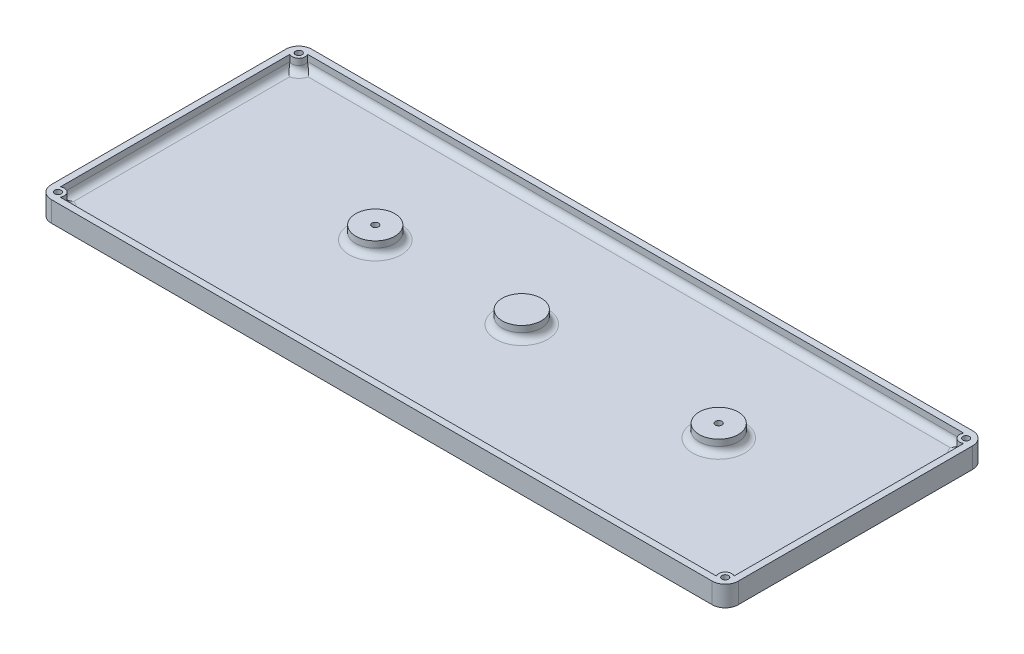
SolidWorks part; units mm, degrees
ref_plane "Front Plane" through (0, 0, 0) normal (0, 0, 1) x (1, 0, 0)
ref_plane "Top Plane" through (0, 0, 0) normal (0, 1, 0) x (1, 0, 0)
ref_plane "Right Plane" through (0, 0, 0) normal (1, 0, 0) x (0, 0, -1)
sketch "Sketch1" plane through (0, 0, 0) normal (0, 1, 0) x (1, 0, 0)
  line L1 (-128.905, 50.8) -> (128.905, 50.8)
  line L2 (-133.985, 45.72) -> (-133.985, -45.72)
  line L3 (-128.905, -50.8) -> (128.905, -50.8)
  line L4 (133.985, 45.72) -> (133.985, -45.72)
  line L5 (-133.985, 50.8) -> (133.985, -50.8) construction
  line L6 (-133.985, -50.8) -> (133.985, 50.8) construction
  arc A0 (-133.985, -45.72) -> (-128.905, -50.8) centre (-128.905, -45.72) ccw
  arc A1 (128.905, -50.8) -> (133.985, -45.72) centre (128.905, -45.72) ccw
  arc A2 (128.905, 50.8) -> (133.985, 45.72) centre (128.905, 45.72) cw
  arc A3 (-128.905, 50.8) -> (-133.985, 45.72) centre (-128.905, 45.72) ccw
  point P0 (0, 0)
  dimension "D3" = 5.08
  dimension "D1" = 101.6
  dimension "D2" = 267.97
extrude "Boss-Extrude1" add sketch "Sketch1" along normal blind 3
sketch "Sketch2" plane through (0, 3, 0) normal (0, 1, 0) x (1, 0, 0)
  line L8 (-128.905, -48.26) -> (128.905, -48.26)
  line L9 (131.445, -45.72) -> (131.445, 45.72)
  line L10 (128.905, 48.26) -> (-128.905, 48.26)
  line L11 (-131.445, 45.72) -> (-131.445, -45.72)
  line L12 (-128.905, -48.26) -> (128.905, -48.26)
  line L13 (131.445, -45.72) -> (131.445, 45.72)
  line L14 (128.905, 48.26) -> (-128.905, 48.26)
  line L15 (-131.445, 45.72) -> (-131.445, -45.72)
  line L20 (-128.905, -50.8) -> (128.905, -50.8)
  line L21 (133.985, -45.72) -> (133.985, 45.72)
  line L22 (128.905, 50.8) -> (-128.905, 50.8)
  line L23 (-133.985, 45.72) -> (-133.985, -45.72)
  line L24 (-128.905, -50.8) -> (128.905, -50.8)
  line L25 (133.985, -45.72) -> (133.985, 45.72)
  line L26 (128.905, 50.8) -> (-128.905, 50.8)
  line L27 (-133.985, 45.72) -> (-133.985, -45.72)
  arc A8 (-131.445, -45.72) -> (-128.905, -48.26) centre (-128.905, -45.72) ccw
  arc A9 (128.905, -48.26) -> (131.445, -45.72) centre (128.905, -45.72) ccw
  arc A10 (131.445, 45.72) -> (128.905, 48.26) centre (128.905, 45.72) ccw
  arc A11 (-128.905, 48.26) -> (-131.445, 45.72) centre (-128.905, 45.72) ccw
  arc A12 (-131.445, -45.72) -> (-128.905, -48.26) centre (-128.905, -45.72) ccw
  arc A13 (128.905, -48.26) -> (131.445, -45.72) centre (128.905, -45.72) ccw
  arc A14 (131.445, 45.72) -> (128.905, 48.26) centre (128.905, 45.72) ccw
  arc A15 (-128.905, 48.26) -> (-131.445, 45.72) centre (-128.905, 45.72) ccw
  arc A20 (-133.985, -45.72) -> (-128.905, -50.8) centre (-128.905, -45.72) ccw
  arc A21 (128.905, -50.8) -> (133.985, -45.72) centre (128.905, -45.72) ccw
  arc A22 (133.985, 45.72) -> (128.905, 50.8) centre (128.905, 45.72) ccw
  arc A23 (-128.905, 50.8) -> (-133.985, 45.72) centre (-128.905, 45.72) ccw
  arc A24 (-133.985, -45.72) -> (-128.905, -50.8) centre (-128.905, -45.72) ccw
  arc A25 (128.905, -50.8) -> (133.985, -45.72) centre (128.905, -45.72) ccw
  arc A26 (133.985, 45.72) -> (128.905, 50.8) centre (128.905, 45.72) ccw
  arc A27 (-128.905, 50.8) -> (-133.985, 45.72) centre (-128.905, 45.72) ccw
  dimension "D1" = 2.54
  dimension "D2" = 0
extrude "Boss-Extrude2" add sketch "Sketch2" along normal blind 5
sketch "Sketch3" plane through (0, 3, 0) normal (0, 1, 0) x (1, 0, 0)
  line L0 (-128.905, -50.8) -> (128.905, -50.8) construction
  line L1 (-133.985, 45.72) -> (-133.985, -45.72) construction
  line L2 (133.985, -45.72) -> (133.985, 45.72) construction
  line L3 (128.905, 50.8) -> (-128.905, 50.8) construction
  circle A0 centre (-57.15, 3.81) radius 7.62
  circle A1 centre (0, 3.81) radius 7.62
  circle A2 centre (76.835, 3.81) radius 7.62
  circle A3 centre (-57.15, 3.81) radius 1.27
  circle A5 centre (76.835, 3.81) radius 1.27
  circle A6 centre (130.175, -46.99) radius 1.27
  circle A7 centre (130.175, 46.99) radius 1.27
  circle A8 centre (-130.175, 46.99) radius 1.27
  circle A9 centre (-130.175, -46.99) radius 1.27
  circle A10 centre (130.175, 46.99) radius 2.54
  circle A11 centre (-130.175, 46.99) radius 2.54
  circle A12 centre (-130.175, -46.99) radius 2.54
  circle A14 centre (130.175, -46.99) radius 2.54
  dimension "D4" = 15.24
  dimension "D5" = 15.24
  dimension "D6" = 15.24
  dimension "D10" = 2.54
  dimension "D11" = 2.54
  dimension "D12" = 2.54
  dimension "D13" = 2.54
  dimension "D14" = 2.54
  dimension "D15" = 2.54
  dimension "D24" = 5.08
  dimension "D25" = 5.08
  dimension "D26" = 5.08
  dimension "D27" = 5.08
  dimension "D1" = 54.61
  dimension "D2" = 54.61
  dimension "D3" = 54.61
  dimension "D7" = 76.835
  dimension "D8" = 57.15
  dimension "D9" = 57.15
  dimension "D16" = 3.81
  dimension "D17" = 3.81
  dimension "D18" = 3.81
  dimension "D19" = 3.81
  dimension "D20" = 3.81
  dimension "D21" = 3.81
  dimension "D22" = 3.81
  dimension "D23" = 3.81
extrude "Boss-Extrude3" add sketch "Sketch3" along normal blind 5
fillet "Fillet1" radius 2.54 11 edges at (-131.445, 3, 0) (0, 3, -48.26) (131.445, 3, 0) (0, 3, 48.26) (-57.15, 3, 3.81) (0, 3, 3.81) (76.835, 3, 3.81) (-128.3789, 3, 45.1939) (-128.3789, 3, -45.1939) (128.3789, 3, -45.1939) (128.3789, 3, 45.1939)
sketch "Sketch4" plane through (0, 0, 0) normal (0, -1, 0) x (1, 0, 0)
  line L0 (133.985, 45.72) -> (133.985, -45.72) construction
  line L1 (128.905, -50.8) -> (-128.905, -50.8) construction
  line L2 (-133.985, -45.72) -> (-133.985, 45.72) construction
  circle A0 centre (-57.15, -3.81) radius 3
  circle A1 centre (76.835, -3.81) radius 3
  dimension "D1" = 6
  dimension "D2" = 6
  dimension "D3" = 57.15
  dimension "D4" = 46.99
  dimension "D5" = 76.835
  dimension "D6" = 46.99
extrude "Cut-Extrude1" cut sketch "Sketch4" against normal blind 4
fillet "Fillet2" radius 0.635 2 edges at (76.835, 0, -6.81) (-57.15, 0, -6.81)
sketch "Sketch5" plane through (0, 8, 0) normal (0, 1, 0) x (1, 0, 0)
  line L0 (128.905, 50.8) -> (-128.905, 50.8) construction
  line L1 (-133.985, 45.72) -> (-133.985, -45.72) construction
  line L2 (133.985, -45.72) -> (133.985, 45.72) construction
  line L3 (-128.905, -50.8) -> (128.905, -50.8) construction
  circle A0 centre (130.175, 46.99) radius 1.27
  circle A1 centre (130.175, -46.99) radius 1.27
  circle A2 centre (-130.175, -46.99) radius 1.27
  circle A3 centre (-130.175, 46.99) radius 1.27
  dimension "D1" = 2.54
  dimension "D4" = 2.54
  dimension "D5" = 3.81
  dimension "D7" = 2.54
  dimension "D8" = 3.81
  dimension "D10" = 2.54
  dimension "D2" = 3.81
  dimension "D3" = 3.81
  dimension "D6" = 3.81
  dimension "D9" = 3.81
  dimension "D11" = 3.81
extrude "Cut-Extrude2" cut sketch "Sketch5" against normal blind 5
